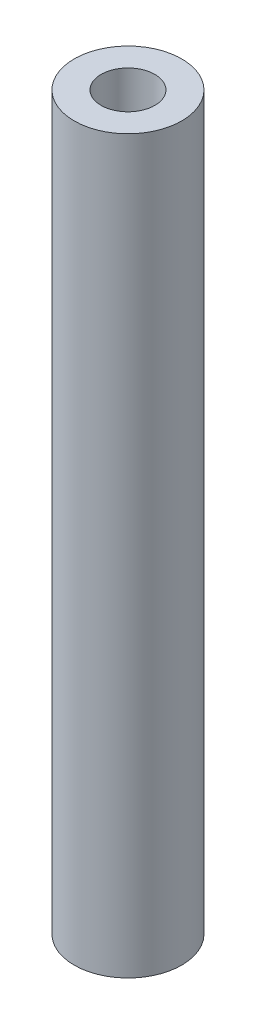
SolidWorks part; units mm, degrees
ref_plane "Front Plane" through (0, 0, 0) normal (0, 0, 1) x (1, 0, 0)
ref_plane "Top Plane" through (0, 0, 0) normal (0, 1, 0) x (1, 0, 0)
ref_plane "Right Plane" through (0, 0, 0) normal (1, 0, 0) x (0, 0, -1)
sketch "Sketch1" plane through (0, 0, 0) normal (0, 1, 0) x (1, 0, 0)
  circle A0 centre (0, 0) radius 2.5
  dimension "D1" = 5
extrude "Boss-Extrude1" add sketch "Sketch1" along normal blind 34
hole_wizard "Tap Drill for M3 Tap1" positions "Sketch2" profile "Sketch3" hole size "M3" standard "DIN"
sketch "Sketch2" plane through (0, 34, 0) normal (0, 1, 0) x (1, 0, 0)
  point P0 (0, 0)
sketch "Sketch3" plane through (0, 34, 0) normal (1, 0, 0) x (0, 0, 1)
  line L0 (0, 0) -> (0, 8.7511)
  line L1 (0, 8.7511) -> (1.25, 8)
  line L2 (1.25, 8) -> (1.25, 0)
  line L5 (1.25, 0) -> (0, 0)
  line L10 (0, 8.7511) -> (-1.25, 8) construction
  line L11 (0, -6.35) -> (0, 107.95) construction
  dimension "Hole Dia." = 2.5
  dimension "Hole Depth" = 8
  dimension "Drill Angle" = 118
hole_wizard "Tap Drill for M3 Tap2" positions "Sketch4" profile "Sketch5" hole size "M3" standard "DIN"
sketch "Sketch4" plane through (0, 0, 0) normal (0, -1, 0) x (-1, 0, 0)
  point P0 (0, 0)
sketch "Sketch5" plane through (0, 0, 0) normal (1, 0, 0) x (0, 0, -1)
  line L0 (0, 0) -> (0, 8.7511)
  line L1 (0, 8.7511) -> (1.25, 8)
  line L2 (1.25, 8) -> (1.25, 0)
  line L5 (1.25, 0) -> (0, 0)
  line L10 (0, 8.7511) -> (-1.25, 8) construction
  line L11 (0, -6.35) -> (0, 107.95) construction
  dimension "Hole Dia." = 2.5
  dimension "Hole Depth" = 8
  dimension "Drill Angle" = 118
